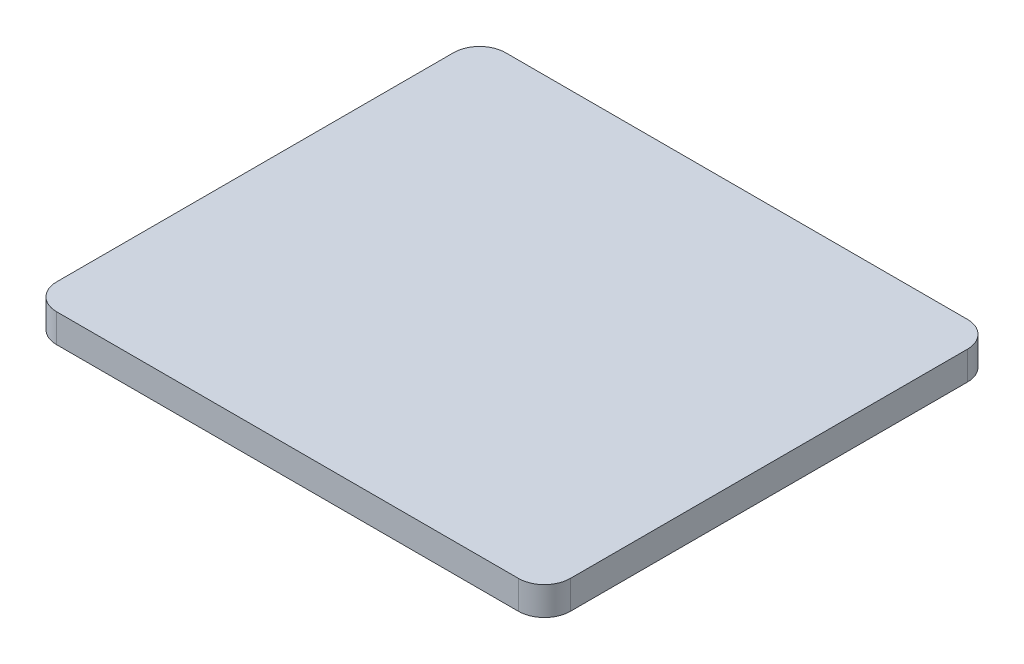
SolidWorks part; units mm, degrees
ref_plane "Front Plane" through (0, 0, 0) normal (0, 0, 1) x (1, 0, 0)
ref_plane "Top Plane" through (0, 0, 0) normal (0, 1, 0) x (1, 0, 0)
ref_plane "Right Plane" through (0, 0, 0) normal (1, 0, 0) x (0, 0, -1)
sketch "Sketch1" plane through (0, 0, 0) normal (0, 1, 0) x (1, 0, 0)
  line L1 (-99, 86.5) -> (99, 86.5)
  line L2 (-99, 86.5) -> (-99, -86.5)
  line L3 (-99, -86.5) -> (99, -86.5)
  line L4 (99, 86.5) -> (99, -86.5)
  line L5 (0, -86.5) -> (0, 86.5) construction
  line L6 (-99, 0) -> (99, 0) construction
  point P4 (0, 0)
  point P144 (0, 0)
  dimension "D1" = 198
  dimension "D2" = 173
extrude "Boss-Extrude1" add sketch "Sketch1" along normal blind 11
fillet "Fillet1" radius 10 4 edges at (-99, 5.5, 86.5) (99, 5.5, 86.5) (99, 5.5, -86.5) (-99, 5.5, -86.5)
sketch "Sketch2" plane through (0, 0, 0) normal (0, -1, 0) x (1, 0, 0)
  line L0 (-89, 86.5) -> (89, 86.5) construction
  line L1 (-71, 57.5) -> (-59, 57.5)
  line L2 (-71, 57.5) -> (-71, 51)
  line L3 (-71, 51) -> (-59, 51)
  line L4 (-59, 57.5) -> (-59, 51)
  line L5 (-65, 51) -> (-65, 57.5) construction
  line L6 (-71, 54.25) -> (-59, 54.25) construction
  line L7 (-42.2, 57.5) -> (-30.2, 57.5)
  line L8 (-42.2, 57.5) -> (-42.2, 51)
  line L9 (-42.2, 51) -> (-30.2, 51)
  line L10 (-30.2, 57.5) -> (-30.2, 51)
  line L11 (-36.2, 51) -> (-36.2, 57.5) construction
  line L12 (-42.2, 54.25) -> (-30.2, 54.25) construction
  line L13 (-71, 35.9) -> (-55, 35.9)
  line L14 (-71, 35.9) -> (-71, 19.8)
  line L15 (-71, 19.8) -> (-55, 19.8)
  line L16 (-55, 35.9) -> (-55, 19.8)
  line L17 (-63, 19.8) -> (-63, 35.9) construction
  line L18 (-71, 27.85) -> (-55, 27.85) construction
  line L19 (-71, 12.1) -> (-55, 12.1)
  line L20 (-71, 12.1) -> (-71, 5.9)
  line L21 (-71, 5.9) -> (-55, 5.9)
  line L22 (-55, 12.1) -> (-55, 5.9)
  line L23 (-63, 5.9) -> (-63, 12.1) construction
  line L24 (-71, 9) -> (-55, 9) construction
  line L25 (-47.2, 35.9) -> (-23.2, 35.9)
  line L26 (-47.2, 35.9) -> (-47.2, 19.8)
  line L27 (-47.2, 19.8) -> (-23.2, 19.8)
  line L28 (-23.2, 35.9) -> (-23.2, 19.8)
  line L29 (-35.2, 19.8) -> (-35.2, 35.9) construction
  line L30 (-47.2, 27.85) -> (-23.2, 27.85) construction
  line L31 (-47.2, 12.1) -> (-23.2, 12.1)
  line L32 (-47.2, 12.1) -> (-47.2, 5.9)
  line L33 (-47.2, 5.9) -> (-23.2, 5.9)
  line L34 (-23.2, 12.1) -> (-23.2, 5.9)
  line L35 (-35.2, 5.9) -> (-35.2, 12.1) construction
  line L36 (-47.2, 9) -> (-23.2, 9) construction
  line L37 (-15.5, 35.9) -> (15.5, 35.9)
  line L38 (-15.5, 35.9) -> (-15.5, 19.8)
  line L39 (-15.5, 19.8) -> (15.5, 19.8)
  line L40 (15.5, 35.9) -> (15.5, 19.8)
  line L41 (0, 19.8) -> (0, 35.9) construction
  line L42 (-15.5, 27.85) -> (15.5, 27.85) construction
  point P92 (-36.2, 54.25)
  point P104 (-65, 54.25)
  point P126 (-63, 9)
  point P127 (-35.2, 9)
  point P137 (0, 27.85)
  point P143 (-35.2, 27.85)
  point P170 (-63, 27.85)
  dimension "D1" = 16
  dimension "D2" = 24
  dimension "D3" = 7.8
  dimension "D4" = 16.8
  dimension "D5" = 12
  dimension "D6" = 12
  dimension "D7" = 6.5
  dimension "D8" = 15.1
  dimension "D9" = 16.1
  dimension "D10" = 7.7
  dimension "D11" = 6.2
  dimension "D12" = 7.7
  dimension "D13" = 31
  dimension "D14" = 29
extrude "Cut-Extrude1" cut sketch "Sketch2" against normal blind 7
ref_plane "Plane1" through (0, 0, 0) normal (-1, 0, 0) x (0, 0, 1)
mirror "Mirror1" about plane through (0, 0, 0) normal (-1, 0, 0) of "Cut-Extrude1"
